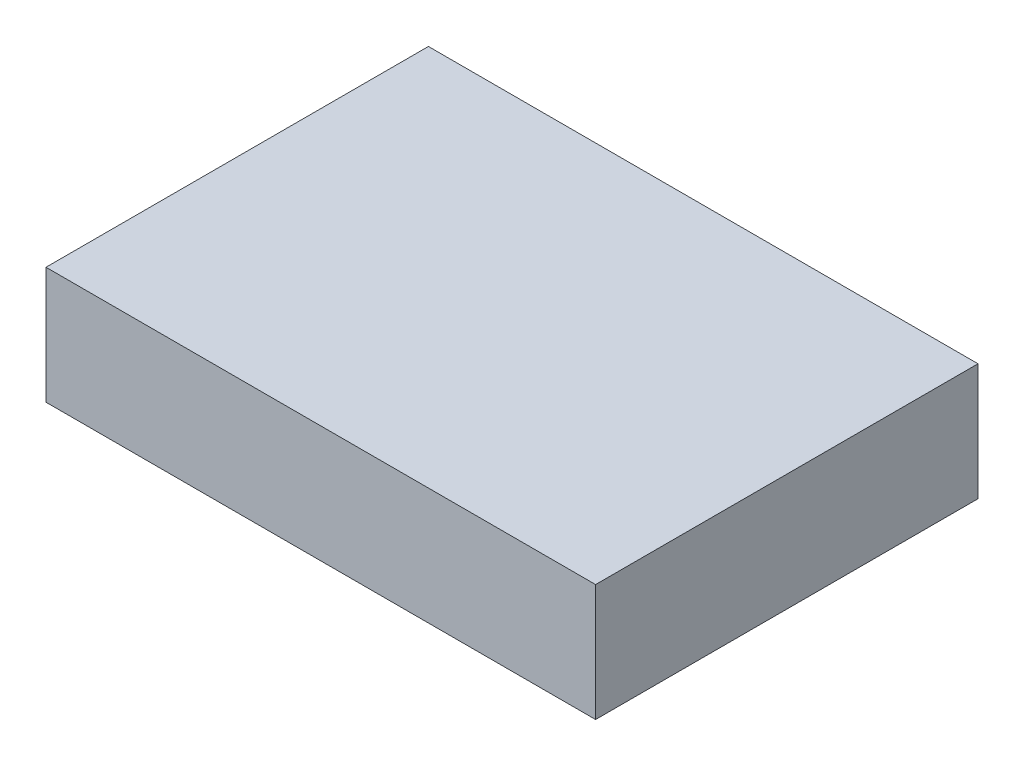
SolidWorks part; units mm, degrees
ref_plane "Ebene vorne" through (0, 0, 0) normal (0, 0, 1) x (1, 0, 0)
ref_plane "Ebene oben" through (0, 0, 0) normal (0, 1, 0) x (1, 0, 0)
ref_plane "Ebene rechts" through (0, 0, 0) normal (1, 0, 0) x (0, 0, -1)
sketch "Skizze1" plane through (0, 0, 0) normal (0, 0, 1) x (1, 0, 0)
  line L1 (0, 0) -> (503, 0)
  line L2 (0, 0) -> (0, 107)
  line L3 (0, 107) -> (503, 107)
  line L4 (503, 0) -> (503, 107)
  dimension "D1" = 503
  dimension "D2" = 107
extrude "Aufsatz-Linear austragen1" add sketch "Skizze1" along normal blind 350
sketch "Skizze2" plane through (0, 0, 0) normal (0, -1, 0) x (1, 0, 0)
  circle A0 centre (84.3996, 294.5556) radius 19
  circle A1 centre (403.7471, 294.5556) radius 19
  circle A2 centre (403.7471, 75.4712) radius 19
  circle A3 centre (84.3996, 75.4712) radius 19
  dimension "D1" = 38
extrude "Aufsatz-Linear austragen2" add sketch "Skizze2" along normal blind 25
